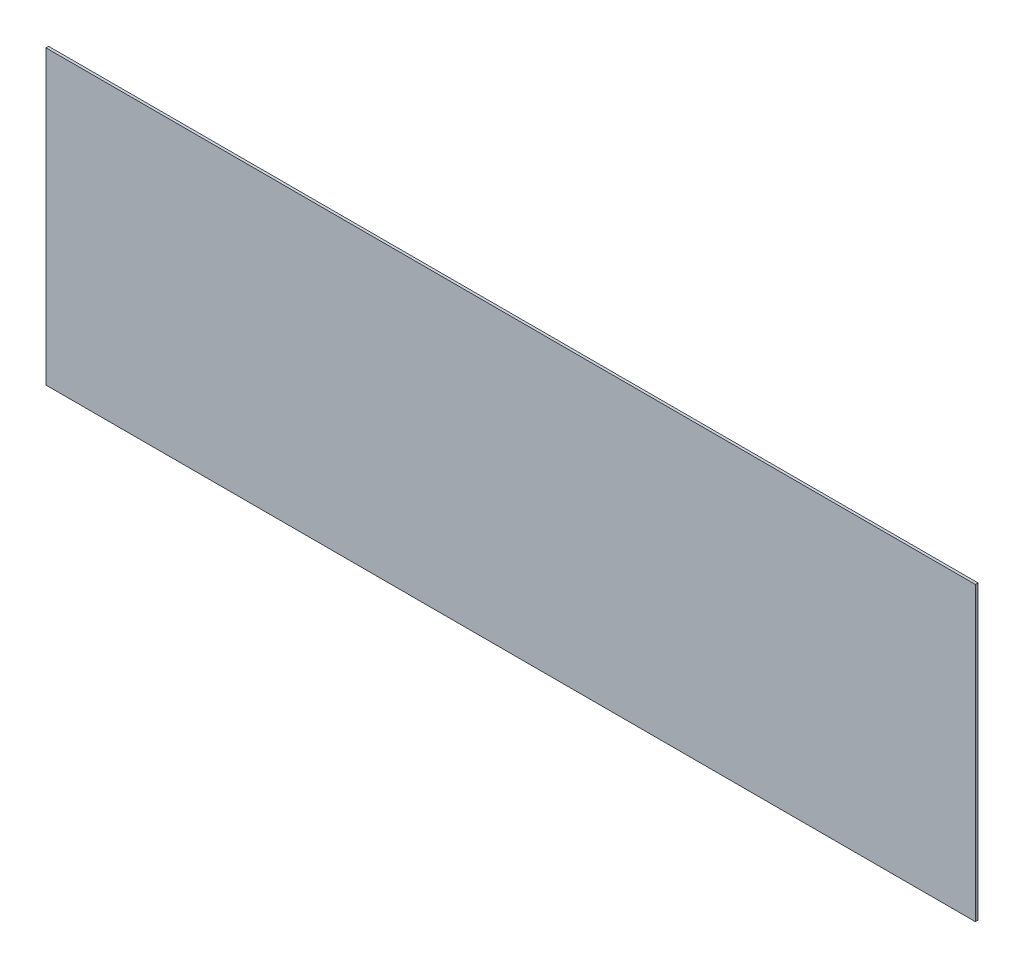
SolidWorks part; units mm, degrees
ref_plane "Plan de face" through (0, 0, 0) normal (0, 0, 1) x (1, 0, 0)
ref_plane "Plan de dessus" through (0, 0, 0) normal (0, 1, 0) x (1, 0, 0)
ref_plane "Plan de droite" through (0, 0, 0) normal (1, 0, 0) x (0, 0, -1)
sketch "Esquisse1" plane through (0, 0, 0) normal (0, 0, 1) x (1, 0, 0)
  line L1 (-34.9827, 16.9762) -> (35.0173, 16.9762)
  line L2 (-34.9827, 16.9762) -> (-34.9827, -5.0238)
  line L3 (-34.9827, -5.0238) -> (35.0173, -5.0238)
  line L4 (35.0173, 16.9762) -> (35.0173, -5.0238)
  dimension "D1" = 70
  dimension "D2" = 22
extrude "Extrusion1" add sketch "Esquisse1" along normal blind 0.2
